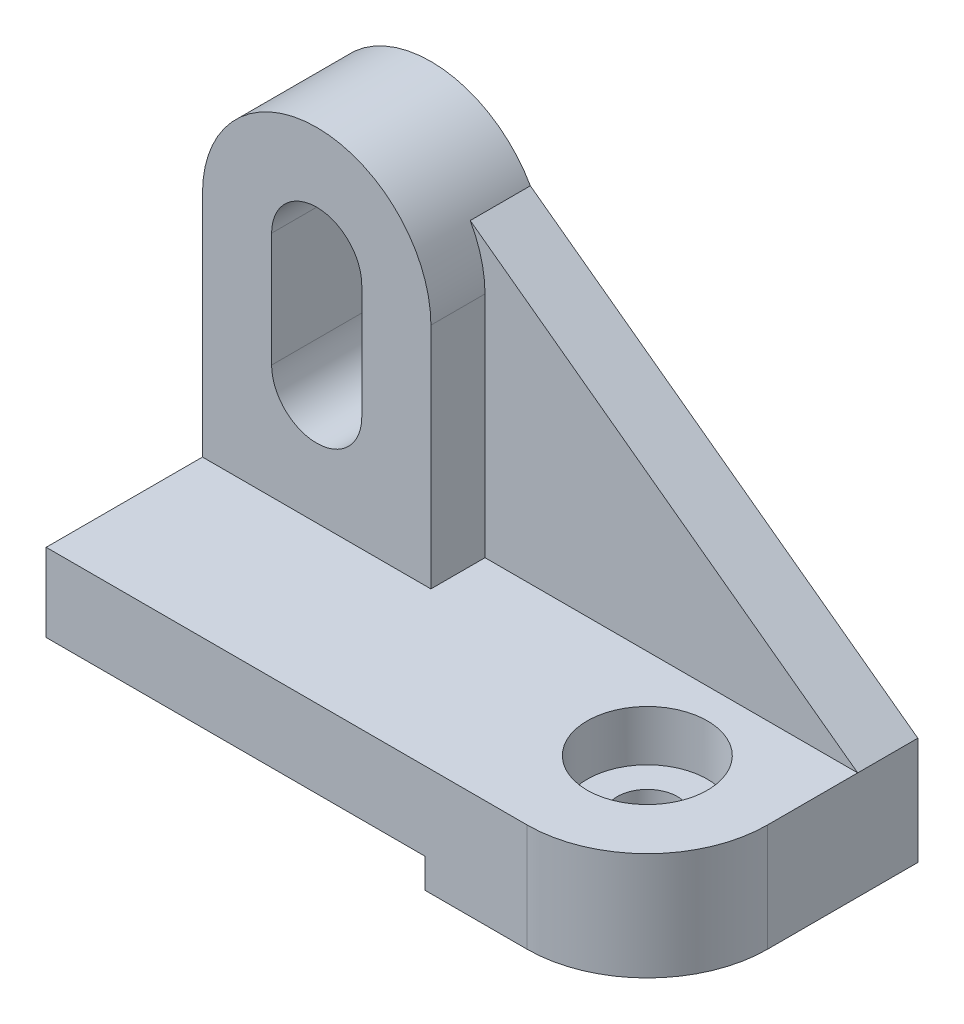
SolidWorks part; units mm, degrees
ref_plane "Front Plane" through (0, 0, 0) normal (0, 0, 1) x (1, 0, 0)
ref_plane "Top Plane" through (0, 0, 0) normal (0, 1, 0) x (1, 0, 0)
ref_plane "Right Plane" through (0, 0, 0) normal (1, 0, 0) x (0, 0, -1)
sketch "Sketch1" plane through (0, 0, 0) normal (0, 0, 1) x (1, 0, 0)
  line L0 (-53.8721, 0) -> (-53.8721, 13)
  line L1 (-53.8721, 13) -> (46.1279, 13)
  line L2 (46.1279, 13) -> (46.1279, -4.9085)
  line L3 (46.1279, -4.9085) -> (9.1279, -4.9085)
  line L4 (9.1279, -4.9085) -> (9.1279, 0)
  line L5 (9.1279, 0) -> (-53.8721, 0)
  dimension "D1" = 100
  dimension "D2" = 63
  dimension "D3" = 13
extrude "Boss-Extrude1" add sketch "Sketch1" against normal blind 45
fillet "Fillet1" radius 20 1 edges at (46.1279, 4.0458, 0)
sketch "Sketch2" plane through (0, 0, -45) normal (0, 0, -1) x (-1, 0, 0)
  line L0 (53.8721, 13) -> (53.8721, 51)
  line L1 (53.8721, 13) -> (15.8721, 13)
  line L2 (-46.1279, 13) -> (53.8721, 13) construction
  line L3 (15.8721, 13) -> (15.8721, 51)
  line L4 (34.8721, 51) -> (34.8721, 32) construction
  line L5 (42.3721, 51) -> (42.3721, 32)
  line L6 (27.3721, 51) -> (27.3721, 32)
  arc A0 (53.8721, 51) -> (15.8721, 51) centre (34.8721, 51) ccw
  arc A1 (42.3721, 51) -> (27.3721, 51) centre (34.8721, 51) ccw
  arc A2 (27.3721, 32) -> (42.3721, 32) centre (34.8721, 32) ccw
  point P8 (34.8721, 41.5)
  dimension "D1" = 19
  dimension "D2" = 19
  dimension "D3" = 19
  dimension "D4" = 15
extrude "Boss-Extrude2" add sketch "Sketch2" against normal blind 19
sketch "Sketch3" plane through (0, 0, -45) normal (0, 0, -1) x (-1, 0, 0)
  line L0 (-46.1279, 13) -> (16.8035, 13)
  line L3 (18.3294, 60.3456) -> (18.3294, 13)
  line L4 (18.3294, 13) -> (16.8035, 13)
  line L5 (-46.1279, 13) -> (18.3294, 60.3456)
  arc A1 (53.8721, 51) -> (15.8721, 51) centre (34.8721, 51) ccw construction
extrude "Boss-Extrude3" add sketch "Sketch3" against normal blind 10 contours L0 L4 L3 L5
sketch "Sketch4" plane through (0, 13, 0) normal (0, 1, 0) x (1, 0, 0)
  circle A0 centre (26.1279, 20) radius 10
  circle A1 centre (26.1279, 20) radius 5
  circle A2 centre (26.1279, 20) radius 3
extrude "Cut-Extrude2" cut sketch "Sketch4" against normal up to next contours A0 A1 | A1 A2 | A2
sketch "Sketch7" plane through (0, -4.9085, 0) normal (0, -1, 0) x (1, 0, 0)
  circle A0 centre (26.1279, -20) radius 10
  circle A1 centre (26.1279, -20) radius 5
  circle M3 centre (26.1279, -20) radius 10
extrude "Boss-Extrude4" add sketch "Sketch7" against normal blind 9.5 contours A1 M3 | A0
